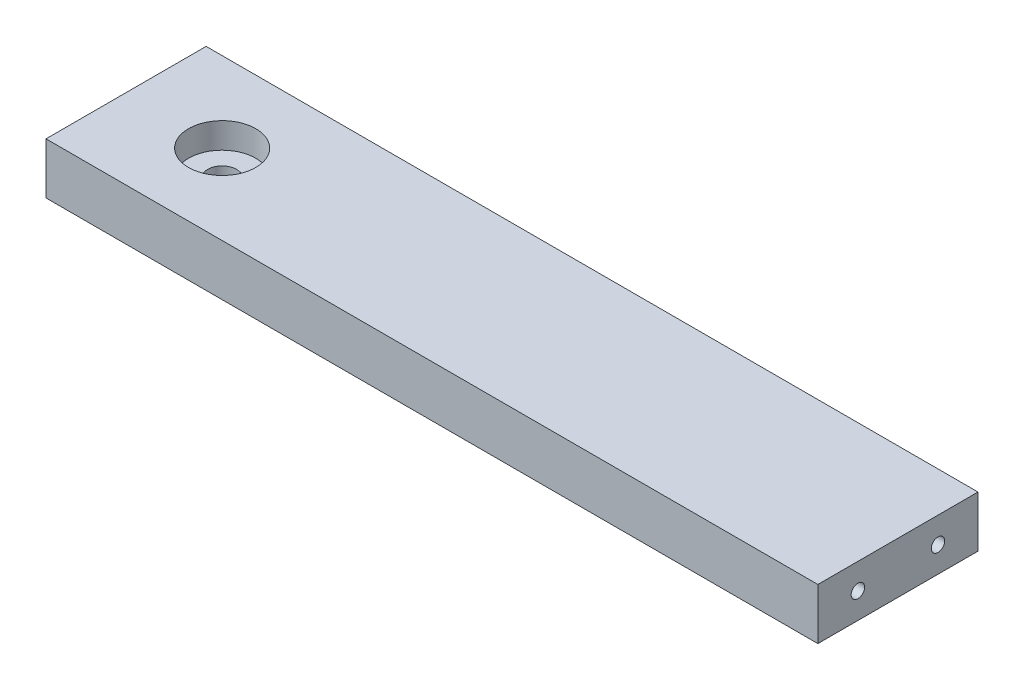
SolidWorks part; units mm, degrees
ref_plane "Front Plane" through (0, 0, 0) normal (0, 0, 1) x (1, 0, 0)
ref_plane "Top Plane" through (0, 0, 0) normal (0, 1, 0) x (1, 0, 0)
ref_plane "Right Plane" through (0, 0, 0) normal (1, 0, 0) x (0, 0, -1)
sketch "Sketch2" plane through (0, 0, 0) normal (0, 1, 0) x (1, 0, 0)
  line L1 (120.5, -25) -> (-120.5, -25)
  line L2 (120.5, -25) -> (120.5, 25)
  line L3 (120.5, 25) -> (-120.5, 25)
  line L4 (-120.5, -25) -> (-120.5, 25)
  line L5 (120.5, -25) -> (-120.5, 25) construction
  line L6 (120.5, 25) -> (-120.5, -25) construction
  point P0 (0, 0)
  dimension "D1" = 241
  dimension "D2" = 50
extrude "Boss-Extrude1" add sketch "Sketch2" along normal blind 16
sketch "Sketch3" plane through (0, 16, 0) normal (0, 1, 0) x (1, 0, 0)
  line L0 (-120.5, 25) -> (-120.5, -25) construction
  line L2 (120.5, 25) -> (-120.5, 25) construction
  circle A0 centre (-90.5, 0) radius 10.5
  dimension "D1" = 21
  dimension "D2" = 30
  dimension "D3" = 25
extrude "Cut-Extrude1" cut sketch "Sketch3" against normal blind 8
sketch "Sketch6" plane through (0, 8, 0) normal (0, 1, 0) x (1, 0, 0)
  circle A0 centre (-90.5, 0) radius 4.5
  dimension "D1" = 9
extrude "Cut-Extrude2" cut sketch "Sketch6" against normal through all
hole_wizard "M5 Tapped Hole4" positions "Sketch20" profile "Sketch21" tap size "M5" standard "ISO"
sketch "Sketch20" plane through (120.5, 0, 0) normal (1, 0, 0) x (0, 0, -1)
  line L0 (-25, 16) -> (25, 16) construction
  line L1 (0, 0) -> (0, 16) construction
  line L2 (-25, 0) -> (25, 0) construction
  point P0 (-12.5, 8)
  point P2 (12.5, 8)
  dimension "D1" = 25
  dimension "D2" = 8
  dimension "D3" = 12.5
sketch "Sketch21" plane through (120.5, 8, 12.5) normal (0, 1, 0) x (0, 0, -1)
  line L0 (0, 0) -> (0, 23.6618)
  line L1 (0, 23.6618) -> (2.1, 22.4)
  line L2 (2.1, 22.4) -> (2.1, 0)
  line L5 (2.1, 0) -> (0, 0)
  line L10 (0, 23.6618) -> (-2.1, 22.4) construction
  line L11 (0, -6.35) -> (0, 107.95) construction
  dimension "Tap Drill Dia." = 4.2
  dimension "Tap Drill Depth" = 22.4
  dimension "Drill Angle" = 118
